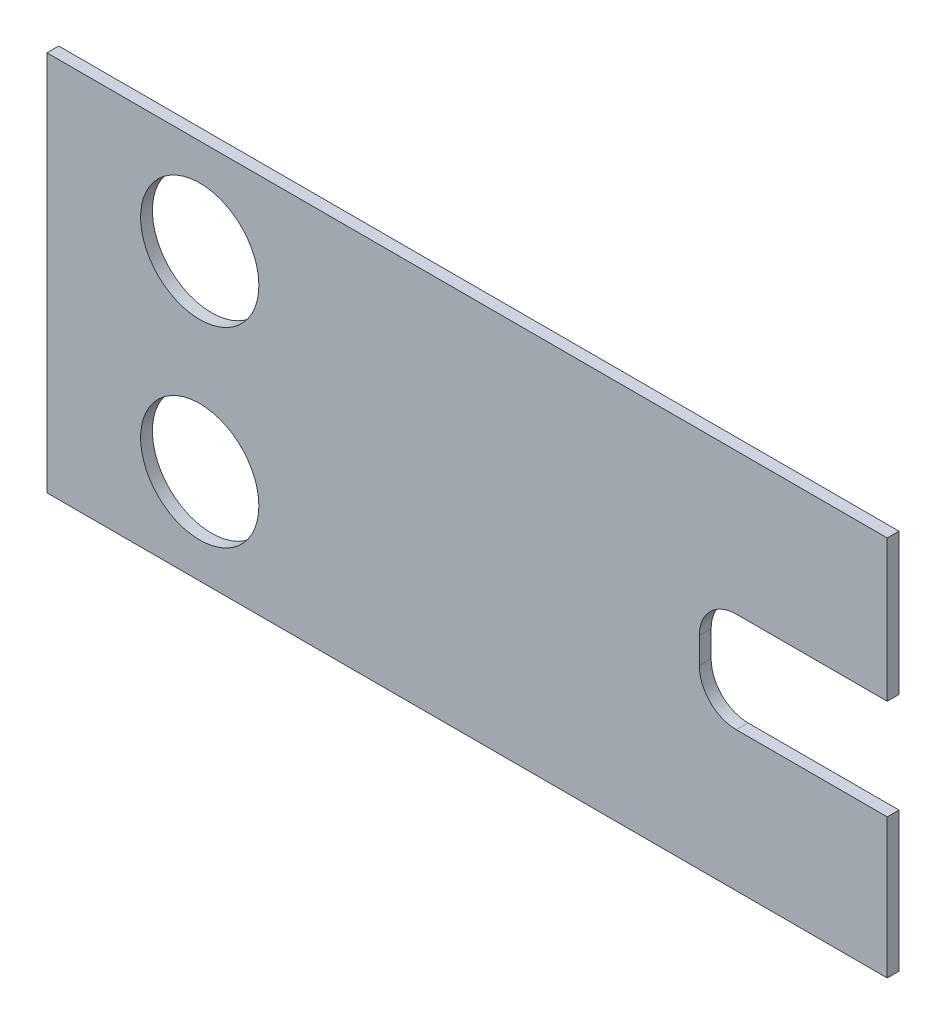
SolidWorks part; units mm, degrees
ref_plane "Front" through (0, 0, 0) normal (0, 0, 1) x (1, 0, 0)
ref_plane "Top" through (0, 0, 0) normal (0, 1, 0) x (1, 0, 0)
ref_plane "Right" through (0, 0, 0) normal (1, 0, 0) x (0, 0, -1)
sketch "Sketch1" plane through (0, 0, 0) normal (0, 0, 1) x (1, 0, 0)
  line L0 (0, 0) -> (0, -15.84)
  line L1 (0, -15.84) -> (34.925, -15.84)
  line L2 (34.925, -15.84) -> (34.925, 0)
  line L3 (34.925, 0) -> (0, 0)
  dimension "D2" = 34.925
  dimension "D4" = 15.84
extrude "Boss-Extrude1" add sketch "Sketch1" along normal mid plane 0.49
sketch "Sketch2" plane through (0, 0, 0.245) normal (0, 0, 1) x (1, 0, 0)
  line L4 (34.925, -5.88) -> (28.6494, -5.88)
  line L5 (34.925, -15.84) -> (34.925, 0) construction
  line L6 (27.115, -7.4144) -> (27.115, -8.5056)
  line L7 (28.6494, -10.04) -> (34.925, -10.04)
  line L8 (34.925, -10.04) -> (34.925, -5.88)
  line L10 (34.925, 0) -> (0, 0) construction
  arc A2 (28.6494, -5.88) -> (27.115, -7.4144) centre (28.6494, -7.4144) ccw
  arc A3 (27.115, -8.5056) -> (28.6494, -10.04) centre (28.6494, -8.5056) ccw
  dimension "D4" = 4.16
  dimension "D6" = 5.88
  dimension "D7" = 2.17
  dimension "D8" = 7.81
extrude "Cut-Extrude1" cut sketch "Sketch2" against normal through all
hole_wizard "#8 Clearance Hole1" positions "Sketch3" profile "Sketch4" hole size "#8" standard "ANSI Inch" end condition through all
sketch "Sketch3" plane through (0, 0, 0.245) normal (0, 0, 1) x (1, 0, 0)
  line L0 (34.925, 0) -> (0, 0) construction
  line L1 (0, 0) -> (0, -15.84) construction
  point P0 (6.35, -3.9688)
  point P2 (6.35, -11.9062)
  dimension "D1" = 7.9375
  dimension "D2" = 3.9688
  dimension "D3" = 6.35
sketch "Sketch4" plane through (6.35, -3.9688, 0.245) normal (1, 0, 0) x (0, -1, 0)
  line L0 (0, 0) -> (0, 0.49)
  line L1 (0, 0.49) -> (2.4574, 0.49)
  line L2 (2.4574, 0.49) -> (2.4574, 0)
  line L5 (2.4574, 0) -> (0, 0)
  line L11 (0, -6.35) -> (0, 107.95) construction
  dimension "Thru Hole Dia." = 4.9149
  dimension "Thru Hole Depth" = 0.49
